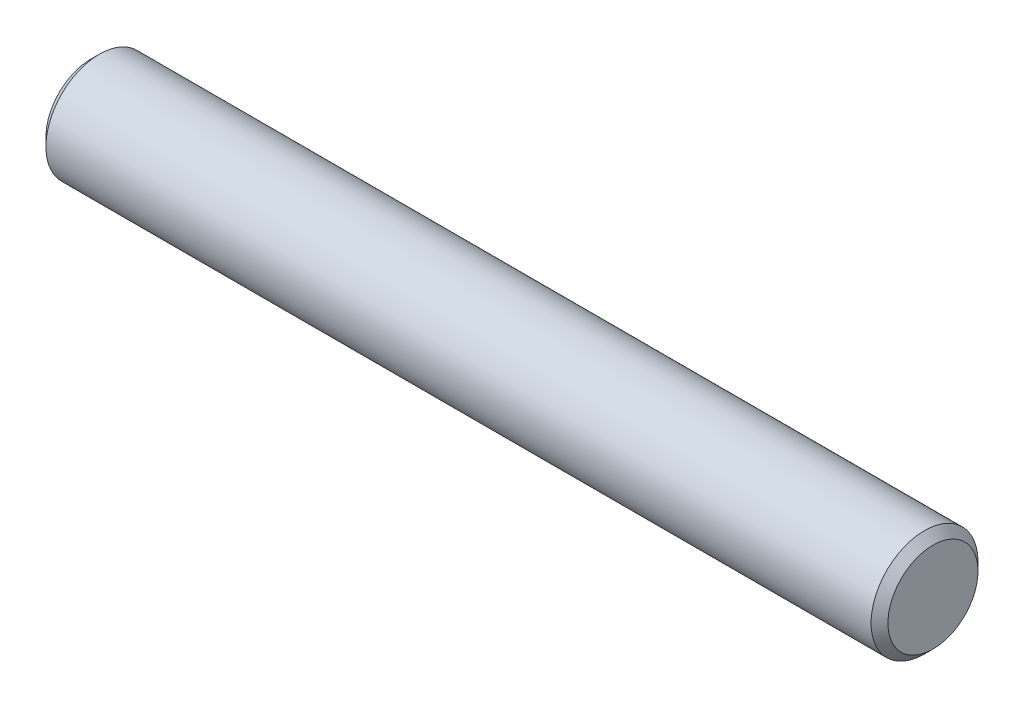
SolidWorks part; units mm, degrees
material "AISI 1045 钢，冷拔"
ref_plane "前视基准面" through (0, 0, 0) normal (0, 0, 1) x (1, 0, 0)
ref_plane "上视基准面" through (0, 0, 0) normal (0, 1, 0) x (1, 0, 0)
ref_plane "右视基准面" through (0, 0, 0) normal (1, 0, 0) x (0, 0, -1)
sketch "草图1" plane through (0, 0, 0) normal (1, 0, 0) x (0, 0, -1)
  circle A0 centre (0, 0) radius 3.175
  dimension "D1" = 6.35
extrude "初始整轴" add sketch "草图1" along normal mid plane 50
chamfer "初始倒角" distance 0.5 angle 45 2 edges at (25, 0, -3.175) (-25, 0, -3.175)
sketch "草图2" [suppressed] plane through (25, 0, 0) normal (1, 0, 0) x (0, 0, -1)
  circle A0 centre (0, 0) radius 2.5
  circle A1 centre (0, 0) radius 3.175
  circle A2 centre (0, 0) radius 3.175 construction
  dimension "右侧凸台直径" = 5
extrude "右侧凸台切除" [suppressed] cut sketch "草图2" against normal blind 5
chamfer "右侧凸台倒角" [suppressed] distance 0.3 angle 45
sketch "草图3" [suppressed] plane through (-25, 0, 0) normal (-1, 0, 0) x (0, 0, 1)
  circle A0 centre (0, 0) radius 2.5
  circle A1 centre (0, 0) radius 3.175
  circle A2 centre (0, 0) radius 3.175 construction
  dimension "左侧凸台直径" = 5
extrude "左侧凸台切除" [suppressed] cut sketch "草图3" against normal blind 5
chamfer "左侧凸台倒角" [suppressed] distance 0.3 angle 45
sketch "草图4" plane through (0, 0, 0) normal (0, 0, 1) x (1, 0, 0)
  line L0 (-13.3489, 0) -> (13.3489, 0) construction
  line L2 (24.5, 3.175) -> (-24.5, 3.175) construction
  line L3 (14.5, 3.175) -> (15.5, 3.175)
  line L4 (14.5, 3.175) -> (14.5, 2.8)
  line L5 (14.5, 2.8) -> (15.5, 2.8)
  line L6 (15.5, 3.175) -> (15.5, 2.8)
  line L7 (15, 3.175) -> (15, -2.1923) construction
  point P6 (0, 0)
  dimension "D1" = 2.8
  dimension "槽1宽度" = 1
  dimension "槽1中心距离" = 15
revolve "卡簧槽1" [suppressed] cut sketch "草图4" angle 360 about L0
sketch "草图5" plane through (0, 0, 0) normal (0, 0, 1) x (1, 0, 0)
  line L0 (-10.9541, 0) -> (10.9541, 0) construction
  line L3 (-15.5, 3.175) -> (-14.5, 3.175)
  line L4 (-15.5, 3.175) -> (-15.5, 2.8)
  line L5 (-15.5, 2.8) -> (-14.5, 2.8)
  line L6 (-14.5, 3.175) -> (-14.5, 2.8)
  line L7 (-15, 3.175) -> (-15, -2.3192) construction
  line L8 (24.5, 3.175) -> (-24.5, 3.175) construction
  point P6 (0, 0)
  dimension "D1" = 2.8
  dimension "槽2宽度" = 1
  dimension "槽2中心距离" = 15
revolve "卡簧槽2" [suppressed] cut sketch "草图5" angle 360 about L0
sketch "草图6" [suppressed] plane through (25, 0, 0) normal (1, 0, 0) x (0, 0, -1)
  circle A0 centre (0, 0) radius 2
  dimension "右侧攻丝直径" = 4
extrude "右侧攻丝切除" [suppressed] cut sketch "草图6" against normal blind 5
chamfer "右侧攻丝倒角" [suppressed] distance 0.5 angle 45
sketch "草图7" [suppressed] plane through (-25, 0, 0) normal (-1, 0, 0) x (0, 0, 1)
  circle A0 centre (0, 0) radius 2
  dimension "左侧攻丝直径" = 4
extrude "左侧攻丝切除" [suppressed] cut sketch "草图7" against normal blind 5
chamfer "左侧攻丝倒角" [suppressed] distance 0.5 angle 45
other "冻结***"
